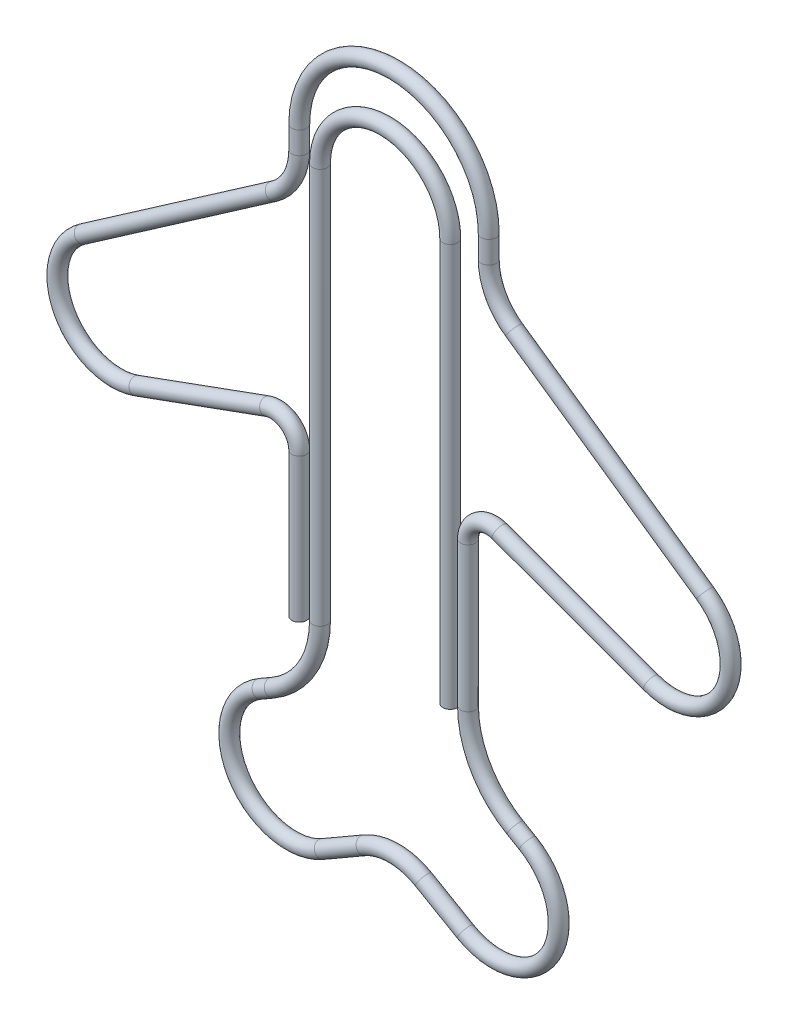
SolidWorks part; units mm, degrees
ref_plane "Спереди" through (0, 0, 0) normal (0, 0, 1) x (1, 0, 0)
ref_plane "Сверху" through (0, 0, 0) normal (0, 1, 0) x (1, 0, 0)
ref_plane "Справа" through (0, 0, 0) normal (1, 0, 0) x (0, 0, -1)
sketch "Эскиз1" plane through (0, 0, 0) normal (0, 0, 1) x (1, 0, 0)
  line L0 (0, -25) -> (0, 25) construction
  line L1 (-12.5, -25) -> (-12.5, 25) construction
  line L2 (12.5, -25) -> (12.5, 25) construction
  line L3 (0, -25) -> (17.3205, -35) construction
  line L4 (5.25, -15.9067) -> (22.5705, -25.9067) construction
  line L5 (-5.25, -34.0933) -> (12.0705, -44.0933) construction
  line L6 (0, -25) -> (-17.3205, -35) construction
  line L7 (5.25, -34.0933) -> (-12.0705, -44.0933) construction
  line L8 (-5.25, -15.9067) -> (-22.5705, -25.9067) construction
  line L9 (0, 60) -> (0, 0) construction
  line L10 (16, 60) -> (16, 0) construction
  line L11 (-16, 60) -> (-16, 0) construction
  line L12 (16, 51) -> (52.5684, 25.6226) construction
  line L13 (43.4469, 8.0101) -> (16, 18) construction
  line L14 (0, 60) -> (0, 72.8205) construction
  line L15 (-43.4469, 8.0101) -> (-16, 18) construction
  line L16 (-16, 51) -> (-52.5684, 25.6226) construction
  line L18 (-12.5, 25) -> (-12.5, 56) construction
  line L19 (9.5, 56) -> (9.5, -12) construction
  arc A0 (-12.5, -25) -> (12.5, -25) centre (0, -25) ccw construction
  arc A1 (12.5, 25) -> (-12.5, 25) centre (0, 25) ccw construction
  arc A2 (5.25, -15.9067) -> (-5.25, -34.0933) centre (0, -25) ccw construction
  arc A3 (12.0705, -44.0933) -> (22.5705, -25.9067) centre (17.3205, -35) ccw construction
  arc A4 (5.25, -34.0933) -> (-5.25, -15.9067) centre (0, -25) ccw construction
  arc A5 (-22.5705, -25.9067) -> (-12.0705, -44.0933) centre (-17.3205, -35) ccw construction
  arc A6 (16, 60) -> (-16, 60) centre (0, 60) ccw construction
  arc A7 (-16, 0) -> (16, 0) centre (0, 0) ccw construction
  arc A8 (-43.4469, 8.0101) -> (-52.5684, 25.6226) centre (-46.8671, 17.4071) cw construction
  arc A9 (43.4469, 8.0101) -> (52.5684, 25.6226) centre (46.8671, 17.4071) ccw construction
  arc A10 (-12.5, 56) -> (9.5, 56) centre (-1.5, 56) cw construction
  point P2 (0, 0)
  point P10 (8.6603, -30)
  point P15 (-8.6603, -30)
  point P24 (0, 30)
  point P39 (-116, -18.397)
  point P42 (116, -18.397)
  point P47 (0, -37.1244)
  dimension "D4" = 21
  dimension "D12" = 10
  dimension "D13" = 11
  dimension "D1" = 50
  dimension "D2" = 25
  dimension "D3" = 20
  dimension "D5" = 120
  dimension "D6" = 32
  dimension "D7" = 30
  dimension "D8" = 18
  dimension "D9" = 70
  dimension "D10" = 100
  dimension "D11" = 33
  dimension "D14" = 68
  dimension "D15" = 4
sketch "Эскиз2" plane through (0, 0, 0) normal (0, 0, 1) x (1, 0, 0)
  line L0 (-12.5, 25) -> (-12.5, 56)
  line L1 (-12.5, 25) -> (-12.5, -10.8549)
  line L2 (-12.5, -25) -> (-12.5, 25) construction
  line L3 (-5.25, -15.9067) -> (-22.5705, -25.9067) construction
  line L4 (-20.5, -24.7113) -> (-22.5705, -25.9067)
  line L5 (-12.0705, -44.0933) -> (-5, -40.0111)
  line L6 (5, -40.0111) -> (12.0705, -44.0933)
  line L7 (22.5705, -25.9067) -> (20.5, -24.7113)
  line L8 (12.5, -25) -> (12.5, 25) construction
  line L9 (5.25, -15.9067) -> (22.5705, -25.9067) construction
  line L10 (12.5, -10.8549) -> (12.5, 13.5613)
  line L11 (43.4469, 8.0101) -> (16, 18) construction
  line L12 (17.8681, 17.3201) -> (43.4469, 8.0101)
  line L13 (52.5684, 25.6226) -> (20.2987, 48.0169)
  line L14 (16, 56.2324) -> (16, 60)
  line L15 (-16, 60) -> (-16, 56.2324)
  line L16 (-20.2987, 48.0169) -> (-52.5684, 25.6226)
  line L17 (-43.4469, 8.0101) -> (-21.3681, 16.0462)
  line L18 (-16, 12.2874) -> (-16, -12)
  line L19 (9.5, 56) -> (9.5, -12)
  arc A0 (-12.5, 56) -> (9.5, 56) centre (-1.5, 56) cw
  arc A1 (-22.5705, -25.9067) -> (-12.0705, -44.0933) centre (-17.3205, -35) ccw
  arc A2 (12.0705, -44.0933) -> (22.5705, -25.9067) centre (17.3205, -35) ccw
  arc A3 (43.4469, 8.0101) -> (52.5684, 25.6226) centre (46.8671, 17.4071) ccw
  arc A4 (16, 60) -> (-16, 60) centre (0, 60) ccw
  arc A5 (-52.5684, 25.6226) -> (-43.4469, 8.0101) centre (-46.8671, 17.4071) ccw
  arc A6 (12.5, 13.5613) -> (17.8681, 17.3201) centre (16.5, 13.5613) cw
  arc A7 (-21.3681, 16.0462) -> (-16, 12.2874) centre (-20, 12.2874) cw
  arc A8 (20.5, -24.7113) -> (12.5, -10.8549) centre (28.5, -10.8549) cw
  arc A9 (-12.5, -10.8549) -> (-20.5, -24.7113) centre (-28.5, -10.8549) cw
  arc A10 (20.2987, 48.0169) -> (16, 56.2324) centre (26, 56.2324) cw
  arc A11 (-16, 56.2324) -> (-20.2987, 48.0169) centre (-26, 56.2324) cw
  arc A12 (-5, -40.0111) -> (5, -40.0111) centre (0, -48.6714) cw
  point P58 (12.5, 19.2739)
  point P61 (-16, 18)
  point P64 (12.5, -20.0925)
  point P67 (-12.5, -20.0925)
  point P70 (16, 51)
  point P73 (-16, 51)
  point P80 (0, -37.1244)
  dimension "D1" = 4
  dimension "D2" = 16
  dimension "D3" = 10
  dimension "D4" = 10
ref_plane "Плоскость1" through (9.5, -12, 0) normal (0, -1, 0) x (-1, 0, 0)
sketch "Эскиз3" plane through (9.5, -12, 0) normal (0, -1, 0) x (-1, 0, 0)
  circle A0 centre (0, 0) radius 1.25
  dimension "D1" = 2.5
sweep "По траектории1" add profiles "Эскиз3" path "Эскиз2"
